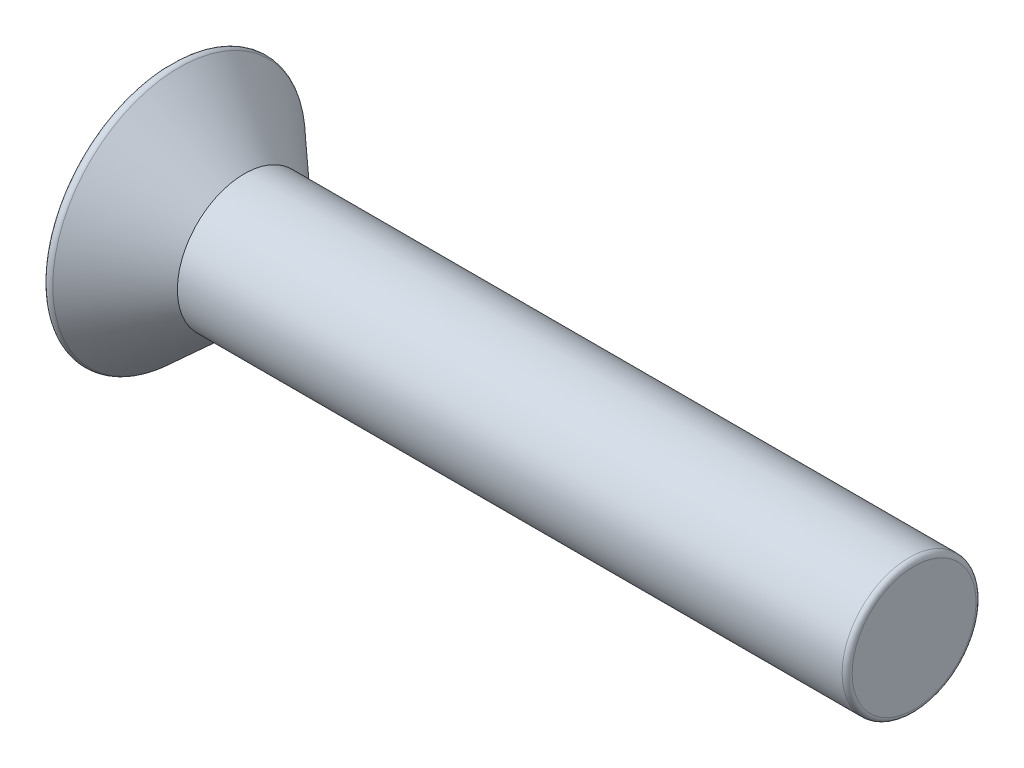
SolidWorks part; units mm, degrees
material "1.0044 (S275JR)"
ref_plane "Ön Düzlem" through (0, 0, 0) normal (0, 0, 1) x (1, 0, 0)
ref_plane "Üst Düzlem" through (0, 0, 0) normal (0, 1, 0) x (1, 0, 0)
ref_plane "Sağ Düzlem" through (0, 0, 0) normal (1, 0, 0) x (0, 0, -1)
sketch "Çizim1" plane through (0, 0, 0) normal (0, 0, 1) x (1, 0, 0)
  line L0 (0, 0) -> (0, 4)
  line L1 (0, 4) -> (-40, 4)
  line L2 (-40, 4) -> (-44.4, 8)
  line L3 (-44.4, 8) -> (-44.4, 0)
  line L4 (-44.4, 0) -> (0, 0)
  dimension "D1" = 4
  dimension "D2" = 40
  dimension "D3" = 8
  dimension "D4" = 4.4
revolve "Döndür1" add sketch "Çizim1" angle 360 about L4
cosmetic thread "Kozmetik Diş Açma1" parameters "D2"=6.619
sketch "Çizim2" plane through (-44.4, 0, 0) normal (-1, 0, 0) x (0, 0, 1)
  line L1 (2.8868, 0) -> (1.4434, 2.5)
  line L2 (1.4434, 2.5) -> (-1.4434, 2.5)
  line L3 (-1.4434, 2.5) -> (-2.8868, 0)
  line L4 (-2.8868, 0) -> (-1.4434, -2.5)
  line L5 (-1.4434, -2.5) -> (1.4434, -2.5)
  line L6 (1.4434, -2.5) -> (2.8868, 0)
  circle A0 centre (0, 0) radius 2.5 construction
  dimension "D1" = 5
extrude "Kes-Ekstrüzyon1" cut sketch "Çizim2" against normal blind 5
fillet "Radyus2" radius 0.3 2 edges at (0, 0, 4) (-44.4, 0, 8)
